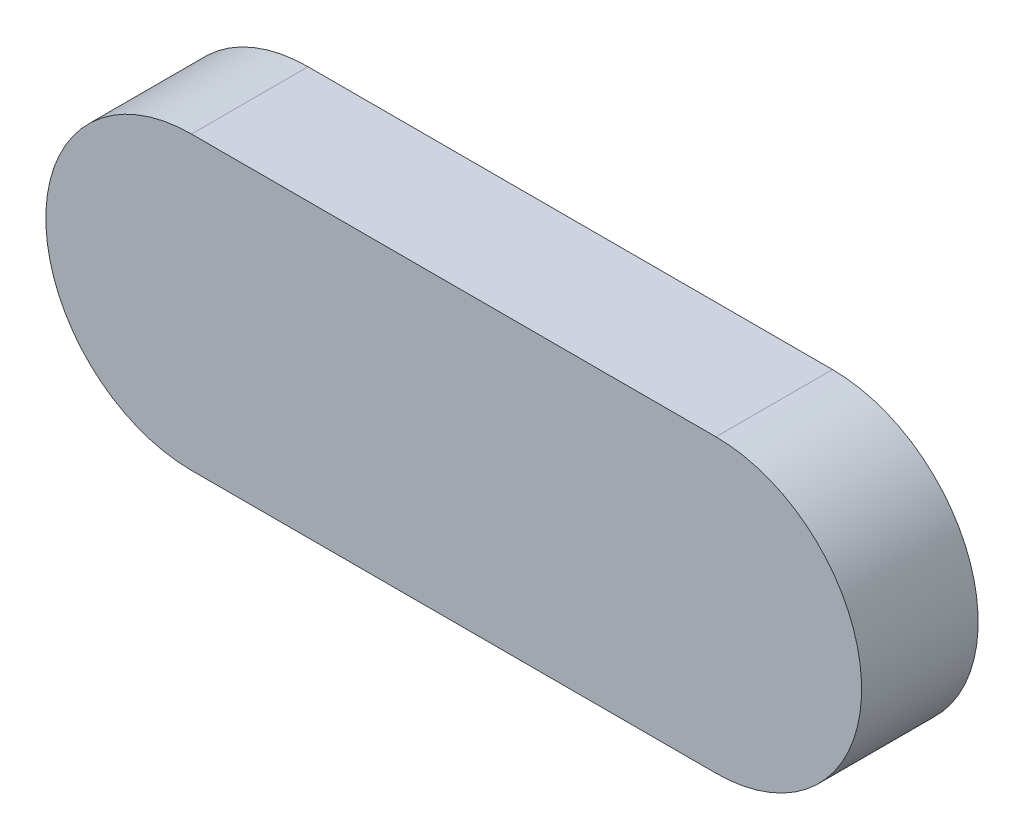
SolidWorks part; units mm, degrees
ref_plane "Piano frontale" through (0, 0, 0) normal (0, 0, 1) x (1, 0, 0)
ref_plane "Piano superiore" through (0, 0, 0) normal (0, 1, 0) x (1, 0, 0)
ref_plane "Piano destro" through (0, 0, 0) normal (1, 0, 0) x (0, 0, -1)
sketch "Schizzo1" plane through (0, 0, 0) normal (0, 0, 1) x (1, 0, 0)
  line L0 (0, 0) -> (36, 0) construction
  line L1 (0, 10) -> (36, 10)
  line L2 (0, -10) -> (36, -10)
  arc A0 (0, 10) -> (0, -10) centre (0, 0) ccw
  arc A1 (36, -10) -> (36, 10) centre (36, 0) ccw
  point P3 (18, 0)
  dimension "D1" = 36
  dimension "D2" = 20
extrude "Estrusione-Estrusione1" add sketch "Schizzo1" along normal blind 8
